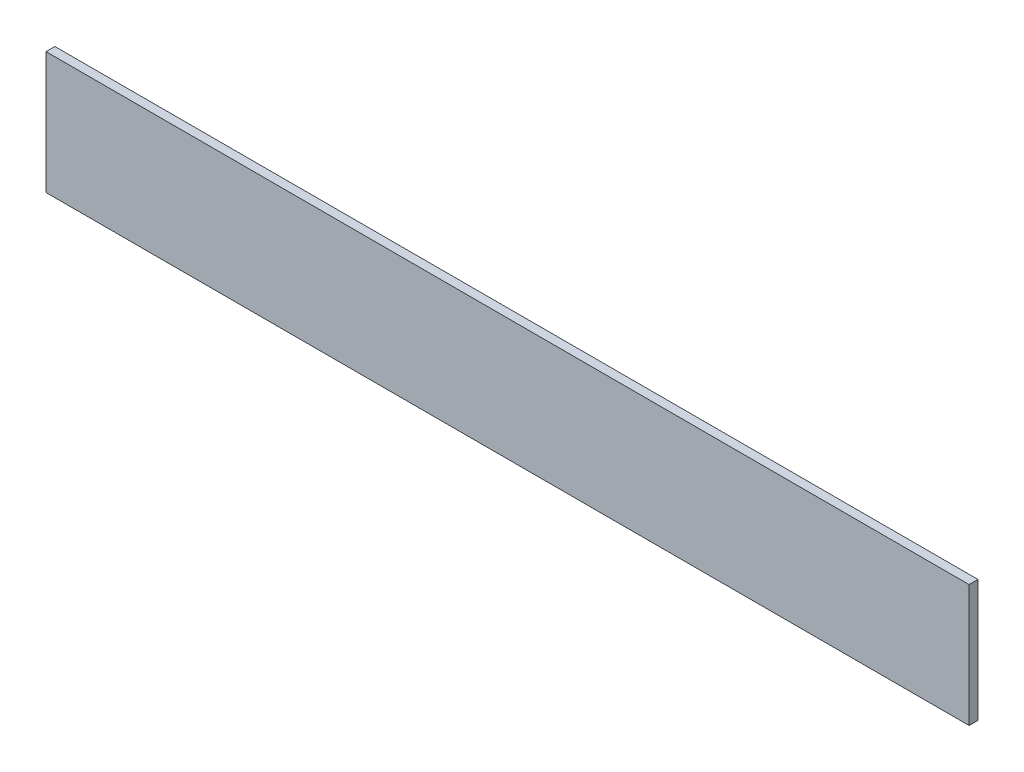
SolidWorks part; units mm, degrees
material "Сплав 2024"
ref_plane "Спереди" through (0, 0, 0) normal (0, 0, 1) x (1, 0, 0)
ref_plane "Сверху" through (0, 0, 0) normal (0, 1, 0) x (1, 0, 0)
ref_plane "Справа" through (0, 0, 0) normal (1, 0, 0) x (0, 0, -1)
sketch "Эскиз1" plane through (0, 0, 0) normal (0, 0, 1) x (1, 0, 0)
  line L1 (-208, 27.5) -> (208, 27.5)
  line L2 (-208, 27.5) -> (-208, -27.5)
  line L3 (-208, -27.5) -> (208, -27.5)
  line L4 (208, 27.5) -> (208, -27.5)
  line L5 (-208, 27.5) -> (208, -27.5) construction
  line L6 (-208, -27.5) -> (208, 27.5) construction
  point P0 (0, 0)
  dimension "D1" = 416
  dimension "D2" = 55
extrude "Бобышка-Вытянуть1" add sketch "Эскиз1" along normal blind 4
